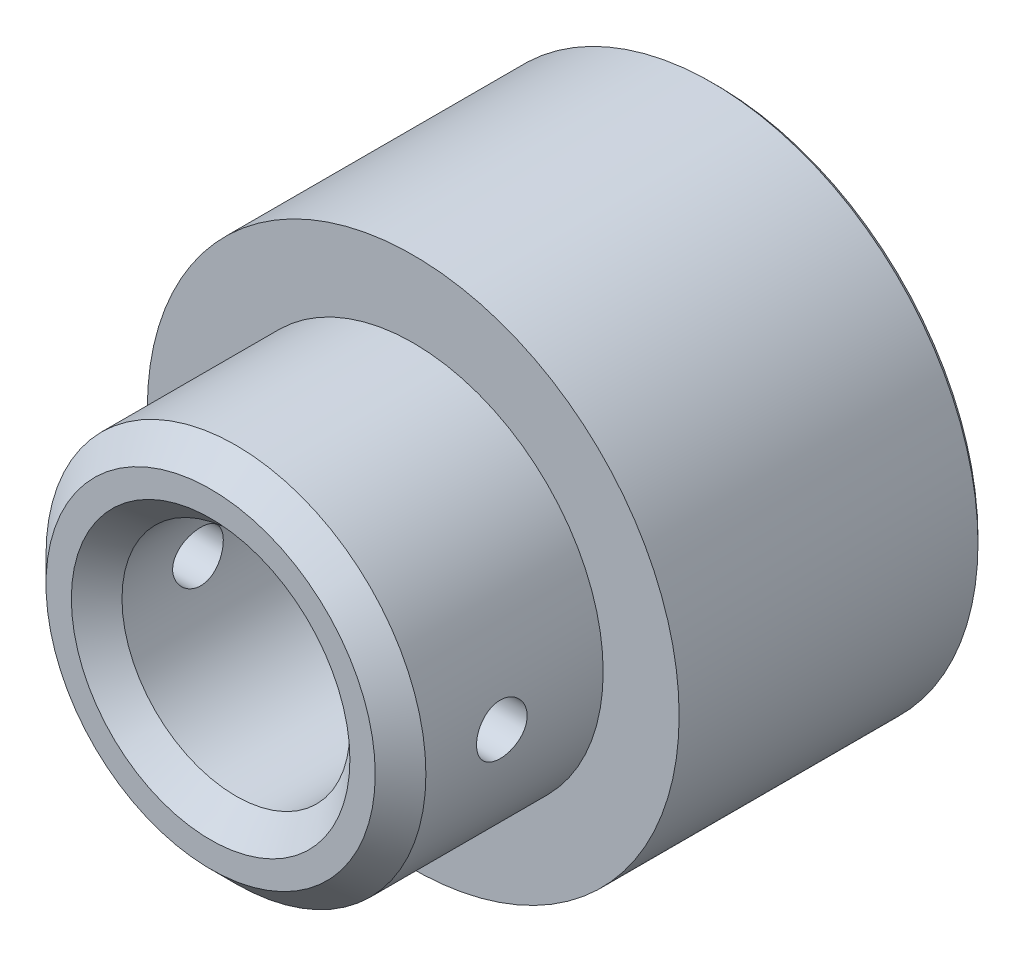
SolidWorks part; units mm, degrees
ref_plane "Спереди" through (0, 0, 0) normal (0, 0, 1) x (1, 0, 0)
ref_plane "Сверху" through (0, 0, 0) normal (0, 1, 0) x (1, 0, 0)
ref_plane "Справа" through (0, 0, 0) normal (1, 0, 0) x (0, 0, -1)
sketch "Эскиз1" plane through (0, 0, 0) normal (0, 0, 1) x (1, 0, 0)
  circle A0 centre (0, 0) radius 52.5
extrude "Бобышка-Вытянуть1" add sketch "Эскиз1" along normal blind 60
sketch "Эскиз2" plane through (0, 0, 60) normal (0, 0, 1) x (1, 0, 0)
  circle A0 centre (0, 0) radius 37.5
extrude "Бобышка-Вытянуть2" add sketch "Эскиз2" along normal blind 40
sketch "Эскиз3" plane through (0, 0, 0) normal (0, 0, -1) x (-1, 0, 0)
  circle A0 centre (0, 0) radius 42.5
extrude "Вырез-Вытянуть1" cut sketch "Эскиз3" against normal blind 40
sketch "Эскиз4" plane through (0, 0, 100) normal (0, 0, 1) x (1, 0, 0)
  circle A0 centre (0, 0) radius 22.5
extrude "Вырез-Вытянуть2" cut sketch "Эскиз4" against normal through all
chamfer "Фаска1" distance 1 angle 45 2 edges at (52.5, 0, 0) (-42.5, 0, 0)
sketch "Эскиз5" plane through (0, 0, 0) normal (1, 0, 0) x (0, 0, -1)
  line L0 (-100, 0) -> (21.8671, 0) construction
  line L1 (-100, 37.5) -> (-100, -37.5) construction
  circle A0 centre (-80, 0) radius 5
  dimension "D1" = 20
extrude "Вырез-Вытянуть3" cut sketch "Эскиз5" against normal through all and the other way through all
chamfer "Фаска2" distance 5 angle 45 2 edges at (37.5, 0, 100) (22.5, 0, 100)
